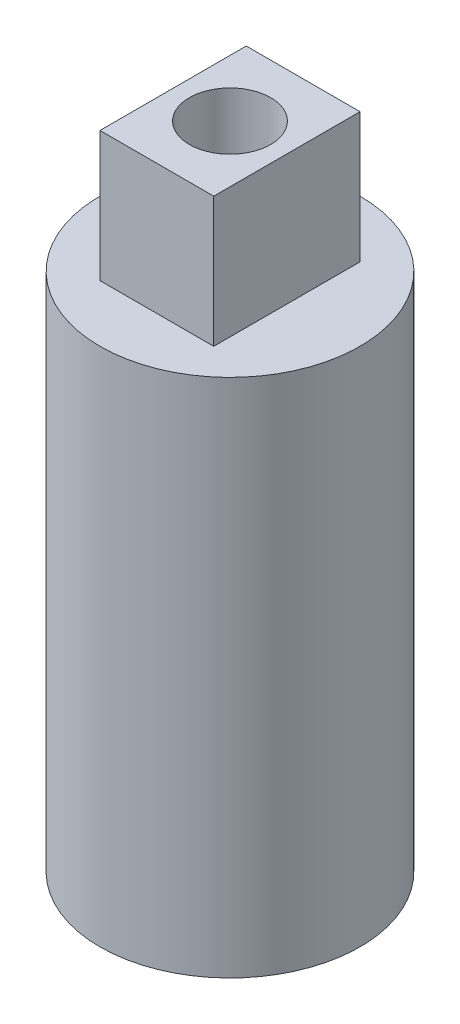
SolidWorks part; units mm, degrees
ref_plane "Спереди" through (0, 0, 0) normal (0, 0, 1) x (1, 0, 0)
ref_plane "Сверху" through (0, 0, 0) normal (0, 1, 0) x (1, 0, 0)
ref_plane "Справа" through (0, 0, 0) normal (1, 0, 0) x (0, 0, -1)
sketch "Эскиз1" plane through (0, 0, 0) normal (0, 1, 0) x (1, 0, 0)
  circle A0 centre (0, 0) radius 40
  dimension "D1" = 80
extrude "Бобышка-Вытянуть1" add sketch "Эскиз1" along normal blind 160
sketch "Эскиз2" plane through (0, 160, 0) normal (0, 1, 0) x (1, 0, 0)
  line L1 (17.5, 22.5) -> (-17.5, 22.5)
  line L2 (17.5, 22.5) -> (17.5, -22.5)
  line L3 (17.5, -22.5) -> (-17.5, -22.5)
  line L4 (-17.5, 22.5) -> (-17.5, -22.5)
  line L5 (17.5, 22.5) -> (-17.5, -22.5) construction
  line L6 (17.5, -22.5) -> (-17.5, 22.5) construction
  point P0 (0, 0)
  dimension "D1" = 35
  dimension "D2" = 45
extrude "Бобышка-Вытянуть2" add sketch "Эскиз2" along normal blind 40
sketch "Эскиз7" plane through (0, 200, 0) normal (0, 1, 0) x (1, 0, 0)
  circle A0 centre (0, 0) radius 12.5
  dimension "D1" = 25
extrude "Вырез-Вытянуть2" cut sketch "Эскиз7" against normal through all
shell "Оболочка1" thickness 1
